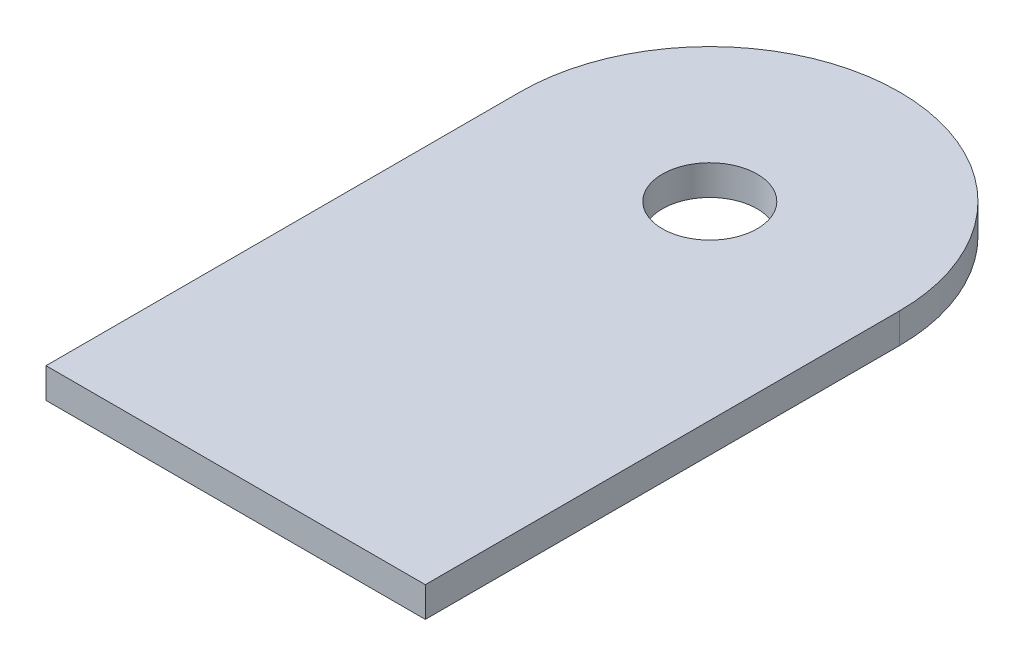
SolidWorks part; units mm, degrees
ref_plane "Front Plane" through (0, 0, 0) normal (0, 0, 1) x (1, 0, 0)
ref_plane "Top Plane" through (0, 0, 0) normal (0, 1, 0) x (1, 0, 0)
ref_plane "Right Plane" through (0, 0, 0) normal (1, 0, 0) x (0, 0, -1)
sketch "Sketch1" plane through (0, 0, 0) normal (0, 1, 0) x (1, 0, 0)
  line L0 (10, 0) -> (10, -25)
  line L1 (10, -25) -> (-10, -25)
  line L2 (-10, -25) -> (-10, 0)
  circle A0 centre (0, 0) radius 2.5
  arc A1 (-10, 0) -> (10, 0) centre (0, 0) cw
  point P4 (-8.5945, 0.7356)
  point P7 (0, 0)
  point P8 (0, 0)
  dimension "D1" = 5
  dimension "D2" = 25
  dimension "D3" = 20
extrude "Boss-Extrude1" add sketch "Sketch1" along normal blind 1.5875
